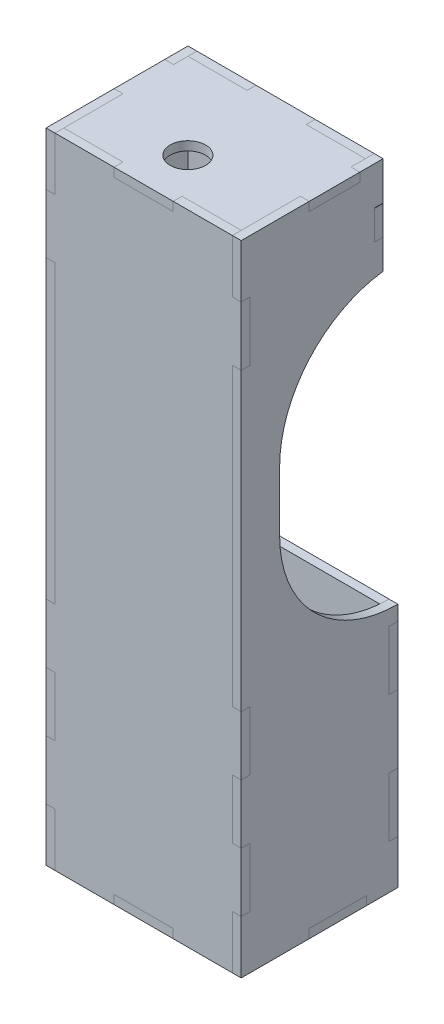
SolidWorks part; units mm, degrees
ref_plane "Front Plane" through (0, 0, 0) normal (0, 0, 1) x (1, 0, 0)
ref_plane "Top Plane" through (0, 0, 0) normal (0, 1, 0) x (1, 0, 0)
ref_plane "Right Plane" through (0, 0, 0) normal (1, 0, 0) x (0, 0, -1)
sketch "Sketch1" plane through (0, 0, 0) normal (0, 0, 1) x (1, 0, 0)
  line L0 (0, 0) -> (0, 100)
  line L1 (0, 100) -> (-3, 100)
  line L2 (-3, 100) -> (-3, 120)
  line L3 (-3, 120) -> (0, 120)
  line L4 (0, 120) -> (0, 138)
  line L5 (0, 138) -> (20, 138)
  line L6 (20, 138) -> (20, 135)
  line L7 (20, 135) -> (40, 135)
  line L8 (40, 135) -> (40, 138)
  line L9 (40, 138) -> (60, 138)
  line L10 (60, 138) -> (60, 120)
  line L11 (63, 120) -> (60, 120)
  line L12 (63, 120) -> (63, 100)
  line L13 (63, 100) -> (60, 100)
  line L14 (60, 100) -> (60, 0)
  line L15 (60, 0) -> (63, 0)
  line L16 (63, 0) -> (63, -20)
  line L17 (63, -20) -> (60, -20)
  line L18 (60, -20) -> (60, -40)
  line L19 (60, -40) -> (63, -40)
  line L20 (63, -40) -> (63, -60)
  line L21 (63, -60) -> (60, -60)
  line L22 (60, -60) -> (60, -78)
  line L23 (60, -78) -> (40, -78)
  line L24 (0, -78) -> (0, -60)
  line L25 (0, -60) -> (-3, -60)
  line L26 (-3, -60) -> (-3, -40)
  line L27 (-3, -40) -> (0, -40)
  line L28 (0, -40) -> (0, -20)
  line L29 (0, -20) -> (-3, -20)
  line L30 (-3, -20) -> (-3, 0)
  line L31 (-3, 0) -> (0, 0)
  line L32 (20, -78) -> (20, -75)
  line L33 (20, -75) -> (40, -75)
  line L34 (40, -75) -> (40, -78)
  line L35 (20, -78) -> (0, -78)
  dimension "D1" = 18
  dimension "D2" = 18
  dimension "D3" = 18
  dimension "D4" = 18
  dimension "D5" = 3
  dimension "D6" = 216
  dimension "D7" = 60
extrude "Boss-Extrude1" add sketch "Sketch1" along normal blind 3
sketch "Sketch2" plane through (63, 0, 0) normal (1, 0, 0) x (0, 0, -1)
  line L0 (45, 138) -> (37.099, 138)
  line L1 (45, 138) -> (45, 125)
  line L3 (10, 65.3137) -> (10, 45)
  line L5 (50, 5) -> (50, 0)
  line L6 (50, -78) -> (39.3312, -78)
  line L7 (0, 0) -> (0, 100) construction
  line L8 (-3, 138) -> (-3, 120)
  line L9 (-3, 120) -> (0, 120)
  line L10 (0, 120) -> (0, 100)
  line L11 (0, 100) -> (-3, 100)
  line L12 (-3, 100) -> (-3, 0)
  line L13 (-3, 0) -> (0, 0)
  line L14 (0, 0) -> (0, -20)
  line L15 (0, -20) -> (-3, -20)
  line L16 (-3, -20) -> (-3, -40)
  line L17 (-3, -40) -> (0, -40)
  line L18 (0, -40) -> (0, -60)
  line L19 (0, -60) -> (-3, -60)
  line L20 (-3, -60) -> (-3, -78)
  line L21 (45, 125) -> (42, 125)
  line L22 (42, 125) -> (42, 115)
  line L23 (42, 115) -> (45, 115)
  line L24 (45, 115) -> (45, 105)
  line L25 (50, 0) -> (47, 0)
  line L26 (47, 0) -> (47, -20)
  line L27 (47, -20) -> (50, -20)
  line L28 (50, -20) -> (50, -43)
  line L29 (50, -43) -> (47, -43)
  line L30 (47, -43) -> (47, -63)
  line L31 (47, -63) -> (50, -63)
  line L32 (50, -63) -> (50, -78)
  line L33 (37.099, 138) -> (37.099, 135)
  line L34 (37.099, 135) -> (20, 135)
  line L35 (20, 135) -> (20, 138)
  line L36 (20, 138) -> (-3, 138)
  line L37 (39.3312, -78) -> (39.3312, -75)
  line L38 (39.3312, -75) -> (20, -75)
  line L39 (20, -75) -> (20, -78)
  line L40 (20, -78) -> (-3, -78)
  arc A0 (10, 45) -> (50, 5) centre (50, 45) ccw
  arc A1 (45, 105) -> (10, 65.3137) centre (50, 65.3137) ccw
  point P12 (39.3312, -75.0891)
  point P13 (13, 7.5947)
  point P14 (0, 0)
  point P17 (13, 107.5947)
  point P60 (0, 0)
  point P63 (44.3638, 107.41)
  point P64 (45, 107.5947)
  point P65 (45.0959, 107.5947)
  point P66 (0, 0)
  point P67 (0, 0)
  point P68 (0, 0)
  point P69 (37.099, 132.9728)
  point P70 (45, 135)
  dimension "D3" = 40
  dimension "D2" = 100
  dimension "D4" = 42
  dimension "D5" = 10
  dimension "D6" = 10
  dimension "D7" = 10
  dimension "D8" = 3
  dimension "D9" = 3
  dimension "D10" = 3
  dimension "D11" = 80
  dimension "D12" = 30
  dimension "D13" = 23
  dimension "D14" = 47
  dimension "D15" = 23
extrude "Boss-Extrude2" add sketch "Sketch2" against normal blind 3 separate body
sketch "Sketch3" plane through (0, 138, 0) normal (0, 1, 0) x (1, 0, 0)
  line L0 (60, 37.099) -> (63, 37.099)
  line L1 (20, -3) -> (40, -3)
  line L2 (0, 0) -> (0, 20)
  line L3 (20, 42) -> (20, 45)
  line L4 (60, 0) -> (60, 20)
  line L5 (63, 37.099) -> (63, 20)
  line L6 (63, 20) -> (60, 20)
  line L7 (60, 37.099) -> (60, 42)
  line L8 (40, -3) -> (40, 0)
  line L9 (20, 42) -> (0, 42)
  line L10 (20, 0) -> (20, -3)
  line L11 (20, 0) -> (0, 0)
  line L12 (40, 0) -> (60, 0)
  line L13 (-3, 20) -> (0, 20)
  line L14 (-3, 37.099) -> (-3, 20)
  line L15 (0, 37.099) -> (-3, 37.099)
  line L16 (0, 37.099) -> (0, 42)
  line L17 (20, 45) -> (40, 45)
  line L18 (40, 45) -> (40, 42)
  line L20 (40, 42) -> (60, 42)
  line L25 (60, 45) -> (60, 37.099) construction
  line L26 (60, 45) -> (63, 45) construction
  circle A0 centre (28.9581, 13) radius 6
  point P4 (60, 45)
  point P8 (60, 41.0495)
  point P18 (60, 42.073)
  point P19 (60, 41.0495)
  point P24 (60, 45)
  point P41 (30, -3)
  dimension "D13" = 12
  dimension "D1" = 3
  dimension "D2" = 3
  dimension "D3" = 3
  dimension "D4" = 20
  dimension "D5" = 3
  dimension "D7" = 20
  dimension "D9" = 60
  dimension "D10" = 66
  dimension "D11" = 20
  dimension "D14" = 16
  dimension "D15" = 28.9581
extrude "Boss-Extrude3" add sketch "Sketch3" against normal blind 3 separate body
sketch "Sketch4" plane through (0, 0, -45) normal (0, 0, -1) x (-1, 0, 0)
  line L0 (-63, 124.9084) -> (-60, 125)
  line L1 (-63, 115) -> (-63, 125) construction
  line L2 (-60, 125) -> (-60, 138)
  line L3 (-60, 125) -> (-60, 138) construction
  line L4 (-60, 138) -> (-40, 138)
  line L5 (-40, 138) -> (-40, 135)
  line L6 (-40, 135) -> (-20, 135)
  line L7 (0, 115) -> (0, 105)
  line L8 (3, 115) -> (0, 115)
  line L9 (3, 124.9084) -> (3, 115)
  line L11 (-20, 138) -> (-20, 135)
  line L12 (-63, 124.9084) -> (-63, 115)
  line L13 (-63, 115) -> (-60, 115)
  line L14 (-60, 115) -> (-60, 105)
  line L16 (-60, 105) -> (-60, 115) construction
  line L17 (-60, 105) -> (0, 105)
  line L18 (0, 138) -> (-20, 138)
  line L19 (0, 125) -> (0, 138)
  line L20 (3, 124.9084) -> (0, 125)
  line L21 (-60, 105) -> (-63, 105) construction
extrude "Boss-Extrude4" add sketch "Sketch4" against normal blind 3 separate body
sketch "Sketch5" plane through (0, 0, -50) normal (0, 0, -1) x (-1, 0, 0)
  line L0 (-60, 5) -> (-60, 0)
  line L3 (-60, 0) -> (-63, 0)
  line L4 (-63, 0) -> (-63, -20)
  line L5 (-63, -20) -> (-60, -20)
  line L6 (-60, -20) -> (-60, -43)
  line L7 (-60, -43) -> (-63, -43) construction
  line L8 (-60, -43) -> (-60, -20) construction
  line L9 (-60, -43) -> (-63, -43)
  line L10 (-63, -43) -> (-63, -63)
  line L11 (-63, -63) -> (-60, -63)
  line L12 (-60, -78) -> (-60, -63) construction
  line L13 (-60, -63) -> (-63, -63) construction
  line L14 (-60, -63) -> (-60, -78)
  line L15 (-40, -75) -> (-40, -78) construction
  line L16 (-60, -78) -> (-40, -78)
  line L17 (-20, -78) -> (-20, -75)
  line L18 (0, -78) -> (-20, -78)
  line L19 (0, -63) -> (0, -78)
  line L20 (3, -63) -> (0, -63)
  line L21 (3, -43) -> (3, -63)
  line L22 (0, -43) -> (3, -43)
  line L23 (0, -20) -> (0, -43)
  line L24 (3, -20) -> (0, -20)
  line L25 (3, 0) -> (3, -20)
  line L26 (0, 0) -> (3, 0)
  line L28 (-40, -78) -> (-40, -75)
  line L29 (-40, -75) -> (-20, -75)
  line L30 (0, 5) -> (0, 0)
  line L38 (-40, -78) -> (-60, -78) construction
  line L39 (-60, 5) -> (0, 5)
  line L44 (-20, -75) -> (-40, -75) construction
  point P7 (-30, -75)
  point P36 (-30, -75)
extrude "Boss-Extrude5" add sketch "Sketch5" against normal blind 3 separate body
sketch "Sketch6" plane through (0, -78, 0) normal (0, -1, 0) x (1, 0, 0)
  line L0 (40, -50) -> (40, -47)
  line L1 (40, -47) -> (60, -47)
  line L2 (60, -47) -> (60, -39.3312)
  line L3 (60, -39.3312) -> (63, -39.3312)
  line L4 (63, -39.3312) -> (63, -20)
  line L5 (63, -20) -> (60, -20)
  line L6 (60, -20) -> (60, 0)
  line L7 (60, 0) -> (40, 0)
  line L8 (40, 0) -> (40, 3)
  line L9 (40, 3) -> (20, 3)
  line L10 (20, 0) -> (20, 3)
  line L11 (0, 0) -> (20, 0)
  line L13 (0, -20) -> (0, 0)
  line L14 (-3, -20) -> (0, -20)
  line L15 (-3, -39.3312) -> (-3, -20)
  line L16 (0, -39.3312) -> (-3, -39.3312)
  line L17 (0, -47) -> (0, -39.3312)
  line L18 (40, -50) -> (20, -50)
  line L19 (20, -47) -> (0, -47)
  line L20 (20, -50) -> (20, -47)
  line L25 (40, -50) -> (20, -50) construction
extrude "Boss-Extrude6" add sketch "Sketch6" against normal blind 3 separate body
sketch "Sketch7" plane through (-3, 0, 0) normal (-1, 0, 0) x (0, 0, 1)
  line L38 (3, 138) -> (-20, 138)
  line L39 (-20, 138) -> (-20, 135)
  line L40 (-20, 135) -> (-37.099, 135)
  line L41 (-37.099, 135) -> (-37.099, 138)
  line L42 (-37.099, 138) -> (-45, 138)
  line L43 (-45, 138) -> (-45, 125)
  line L44 (-45, 125) -> (-42, 125)
  line L45 (-42, 125) -> (-42, 115)
  line L46 (-42, 115) -> (-45, 115)
  line L47 (-45, 115) -> (-45, 105)
  line L48 (-10, 65.3137) -> (-10, 45)
  line L49 (-50, 5) -> (-50, 0)
  line L50 (-50, 0) -> (-47, 0)
  line L51 (-47, 0) -> (-47, -20)
  line L52 (-47, -20) -> (-50, -20)
  line L53 (-50, -20) -> (-50, -43)
  line L54 (-50, -43) -> (-47, -43)
  line L55 (-47, -43) -> (-47, -63)
  line L56 (-47, -63) -> (-50, -63)
  line L57 (-50, -63) -> (-50, -78)
  line L58 (-50, -78) -> (-39.3312, -78)
  line L59 (-39.3312, -78) -> (-39.3312, -75)
  line L60 (-39.3312, -75) -> (-20, -75)
  line L61 (-20, -75) -> (-20, -78)
  line L62 (-20, -78) -> (3, -78)
  line L63 (3, -78) -> (3, -60)
  line L64 (3, -60) -> (0, -60)
  line L65 (0, -60) -> (0, -40)
  line L66 (0, -40) -> (3, -40)
  line L67 (3, -40) -> (3, -20)
  line L68 (3, -20) -> (0, -20)
  line L69 (0, -20) -> (0, 0)
  line L70 (0, 0) -> (3, 0)
  line L71 (3, 0) -> (3, 100)
  line L72 (3, 100) -> (0, 100)
  line L73 (0, 100) -> (0, 120)
  line L74 (0, 120) -> (3, 120)
  line L75 (3, 120) -> (3, 138)
  line L76 (3, 138) -> (-20, 138)
  line L77 (-20, 138) -> (-20, 135)
  line L78 (-20, 135) -> (-37.099, 135)
  line L79 (-37.099, 135) -> (-37.099, 138)
  line L80 (-37.099, 138) -> (-45, 138)
  line L81 (-45, 138) -> (-45, 125)
  line L82 (-45, 125) -> (-42, 125)
  line L83 (-42, 125) -> (-42, 115)
  line L84 (-42, 115) -> (-45, 115)
  line L85 (-45, 115) -> (-45, 105)
  line L86 (-10, 65.3137) -> (-10, 45)
  line L87 (-50, 5) -> (-50, 0)
  line L88 (-50, 0) -> (-47, 0)
  line L89 (-47, 0) -> (-47, -20)
  line L90 (-47, -20) -> (-50, -20)
  line L91 (-50, -20) -> (-50, -43)
  line L92 (-50, -43) -> (-47, -43)
  line L93 (-47, -43) -> (-47, -63)
  line L94 (-47, -63) -> (-50, -63)
  line L95 (-50, -63) -> (-50, -78)
  line L96 (-50, -78) -> (-39.3312, -78)
  line L97 (-39.3312, -78) -> (-39.3312, -75)
  line L98 (-39.3312, -75) -> (-20, -75)
  line L99 (-20, -75) -> (-20, -78)
  line L100 (-20, -78) -> (3, -78)
  line L101 (3, -78) -> (3, -60)
  line L102 (3, -60) -> (0, -60)
  line L103 (0, -60) -> (0, -40)
  line L104 (0, -40) -> (3, -40)
  line L105 (3, -40) -> (3, -20)
  line L106 (3, -20) -> (0, -20)
  line L107 (0, -20) -> (0, 0)
  line L108 (0, 0) -> (3, 0)
  line L109 (3, 0) -> (3, 100)
  line L110 (3, 100) -> (0, 100)
  line L111 (0, 100) -> (0, 120)
  line L112 (0, 120) -> (3, 120)
  line L113 (3, 120) -> (3, 138)
  arc A2 (-10, 65.3137) -> (-45, 105) centre (-50, 65.3137) ccw
  arc A3 (-50, 5) -> (-10, 45) centre (-50, 45) ccw
  arc A4 (-10, 65.3137) -> (-45, 105) centre (-50, 65.3137) ccw
  arc A5 (-50, 5) -> (-10, 45) centre (-50, 45) ccw
  dimension "D1" = 0
extrude "Boss-Extrude8" add sketch "Sketch7" against normal blind 3 separate body
